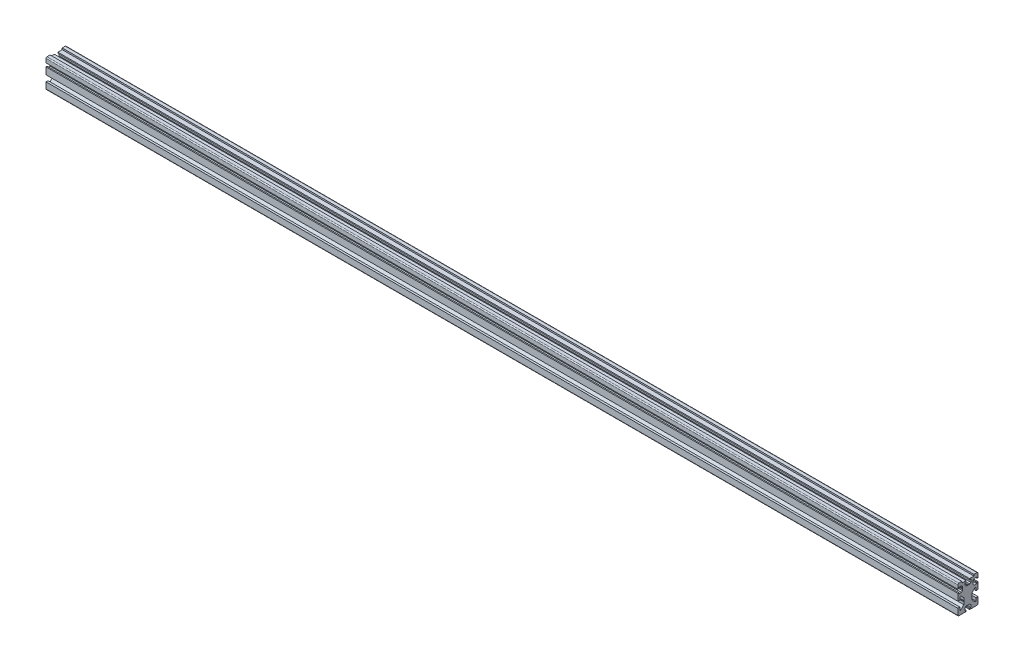
SolidWorks part; units mm, degrees
ref_plane "Front Plane" through (0, 0, 0) normal (0, 0, 1) x (1, 0, 0)
ref_plane "Top Plane" through (0, 0, 0) normal (0, 1, 0) x (1, 0, 0)
ref_plane "Right Plane" through (0, 0, 0) normal (1, 0, 0) x (0, 0, -1)
ref_plane "Plane1" through (24, 0, 0) normal (1, 0, 0) x (0, 0, -1)
ref_plane "Plane2" through (1000, 0, 0) normal (1, 0, 0) x (0, 0, -1)
ref_plane "Plane3" through (925, 0, 0) normal (1, 0, 0) x (0, 0, -1)
ref_plane "Plane4" through (474.5, 0, 0) normal (1, 0, 0) x (0, 0, -1)
sketch "Sketch1" plane through (24, 0, 0) normal (1, 0, 0) x (0, 0, -1)
  line L0 (-5.3, 9.35) -> (-5.3, 8.0196)
  line L1 (-5.3, 8.0196) -> (-5, 7.5)
  line L2 (-5, 7.5) -> (-5.3, 6.9804)
  line L3 (-5.3, 6.9804) -> (-5.3, 5.65)
  line L4 (-5.3, 5.65) -> (-6.3, 4.65)
  line L5 (-6.3, 4.65) -> (-8.9, 4.65)
  line L6 (-8.9, 4.65) -> (-8.9, 5.8)
  line L7 (-8.9, 5.8) -> (-10, 5.8)
  line L8 (-10, 5.8) -> (-10, -1)
  line L9 (-10, -1) -> (-8, -1)
  line L10 (-8, -1) -> (-8, 2)
  line L11 (-8, 2) -> (-7, 2)
  line L12 (-7, 2) -> (-4, -1)
  line L13 (-4, -1) -> (-4, -3.4804)
  line L14 (-4, -3.4804) -> (-3.7, -4)
  line L15 (-3.7, -4) -> (-4, -4.5196)
  line L16 (-4, -4.5196) -> (-4, -7)
  line L17 (-4, -7) -> (-7, -10)
  line L18 (-7, -10) -> (-8, -10)
  line L19 (-8, -10) -> (-8, -7)
  line L20 (-8, -7) -> (-10, -7)
  line L21 (-10, -7) -> (-10, -13)
  line L22 (-9, -14) -> (-1.7, -14)
  line L23 (-1.7, -14) -> (-1.7, -12.9)
  line L24 (-1.7, -12.9) -> (-2.85, -12.9)
  line L25 (-2.85, -12.9) -> (-2.85, -10.3)
  line L26 (-2.85, -10.3) -> (-1.85, -9.3)
  line L27 (-1.85, -9.3) -> (-0.5196, -9.3)
  line L28 (-0.5196, -9.3) -> (0, -9)
  line L29 (0, -9) -> (0.5196, -9.3)
  line L30 (0.5196, -9.3) -> (1.85, -9.3)
  line L31 (1.85, -9.3) -> (2.85, -10.3)
  line L32 (2.85, -10.3) -> (2.85, -12.9)
  line L33 (2.85, -12.9) -> (1.7, -12.9)
  line L34 (1.7, -12.9) -> (1.7, -14)
  line L35 (1.7, -14) -> (9, -14)
  line L36 (10, -13) -> (10, -7)
  line L37 (-5, 7.5) -> (-10, 7.5) construction
  line L38 (-3.7, -4) -> (-10, -4) construction
  line L39 (5, 7.5) -> (10, 7.5) construction
  line L40 (6.3, 10.35) -> (5.3, 9.35)
  line L41 (8.9, 10.35) -> (6.3, 10.35)
  line L42 (8.9, 9.2) -> (8.9, 10.35)
  line L43 (10, 9.2) -> (8.9, 9.2)
  line L44 (8.9, 5.8) -> (10, 5.8)
  line L45 (8.9, 4.65) -> (8.9, 5.8)
  line L46 (6.3, 4.65) -> (8.9, 4.65)
  line L47 (5.3, 5.65) -> (6.3, 4.65)
  line L48 (5.3, 6.9804) -> (5.3, 5.65)
  line L49 (10, -1) -> (10, 5.8)
  line L50 (5, 7.5) -> (5.3, 6.9804)
  line L51 (5.3, 8.0196) -> (5, 7.5)
  line L52 (5.3, 9.35) -> (5.3, 8.0196)
  line L53 (3.7, -4) -> (10, -4) construction
  line L54 (8, -7) -> (10, -7)
  line L55 (8, -10) -> (8, -7)
  line L56 (7, -10) -> (8, -10)
  line L57 (4, -7) -> (7, -10)
  line L58 (4, -4.5196) -> (4, -7)
  line L59 (3.7, -4) -> (4, -4.5196)
  line L60 (4, -3.4804) -> (3.7, -4)
  line L61 (4, -1) -> (4, -3.4804)
  line L62 (7, 2) -> (4, -1)
  line L63 (8, 2) -> (7, 2)
  line L64 (10, 9.2) -> (10, 13)
  line L65 (6, 14) -> (9, 14)
  line L66 (-10, 13) -> (-10, 9.2)
  line L67 (-10, 9.2) -> (-8.9, 9.2)
  line L68 (-8.9, 9.2) -> (-8.9, 10.35)
  line L69 (-8.9, 10.35) -> (-6.3, 10.35)
  line L70 (-6.3, 10.35) -> (-5.3, 9.35)
  line L71 (-1.7, 12.5) -> (-6, 12.5)
  line L72 (-6, 12.5) -> (-6, 14)
  line L73 (-9, 14) -> (-6, 14)
  line L74 (6, 14) -> (6, 12.5)
  line L75 (6, 12.5) -> (1.7, 12.5)
  line L76 (1.7, 12.5) -> (1.7, 11.4)
  line L77 (1.7, 11.4) -> (2.85, 11.4)
  line L78 (2.85, 11.4) -> (2.85, 8.8)
  line L79 (2.85, 8.8) -> (1.85, 7.8)
  line L80 (1.85, 7.8) -> (0.5196, 7.8)
  line L81 (0.5196, 7.8) -> (0, 7.5)
  line L82 (0, 7.5) -> (-0.5196, 7.8)
  line L83 (-0.5196, 7.8) -> (-1.85, 7.8)
  line L84 (-1.85, 7.8) -> (-2.85, 8.8)
  line L85 (-2.85, 8.8) -> (-2.85, 11.4)
  line L86 (-2.85, 11.4) -> (-1.7, 11.4)
  line L87 (-1.7, 11.4) -> (-1.7, 12.5)
  line L88 (10, 0) -> (-10, 0) construction
  line L89 (0, 14) -> (0, -14) construction
  line L90 (11, 0) -> (-11, 0) construction
  line L91 (0, 15.4) -> (0, -15.4) construction
  line L92 (-6, 14) -> (6, 14) construction
  line L93 (-1.7, -14) -> (1.7, -14) construction
  line L94 (8, -1) -> (8, 2)
  line L95 (10, -1) -> (8, -1)
  arc A0 (-10, -13) -> (-9, -14) centre (-9, -13) ccw
  arc A1 (9, -14) -> (10, -13) centre (9, -13) ccw
  arc A2 (10, 13) -> (9, 14) centre (9, 13) ccw
  arc A3 (-9, 14) -> (-10, 13) centre (-9, 13) ccw
  point P46 (0, 12.5)
  dimension "FIX_21" = 2
  dimension "FIX_6" = 1
  dimension "FIX_3" = 14
  dimension "FIX_4" = 28
  dimension "FIX_5" = 20
  dimension "FIX_7" = 12
  dimension "FIX_8" = 1.5
  dimension "FIX_17" = 10
  dimension "FIX_18" = 11.5
  dimension "FIX_19" = 6
  dimension "FIX_20" = 12
  dimension "FIX_22" = 4
extrude "Boss-Extrude1" add sketch "Sketch1" along normal up to surface (901 mm away) up to plane "Plane3"
ref_plane "Plane5" through (0, 0, 10) normal (0, 0, 1) x (1, 0, 0)
sketch "Sketch2" [suppressed] plane through (0, 0, 10) normal (0, 0, 1) x (1, 0, 0)
  line L0 (0, -11) -> (0, 11) construction
  circle A0 centre (85, 7.5) radius 3.55
  dimension "FIX_25" = 7.1
  dimension "FYA" = 85
extrude "Cut-Extrude1" [suppressed] cut sketch "Sketch2" against normal up to surface (1.1 mm away)
sketch "Sketch3" [suppressed] plane through (0, 0, 10) normal (0, 0, 1) x (1, 0, 0)
  circle A0 centre (85, -4) radius 6.05
  dimension "FIX_26" = 12.1
extrude "Cut-Extrude2" [suppressed] cut sketch "Sketch3" against normal up to surface (2 mm away)
sketch "Sketch4" [suppressed] plane through (0, 0, 10) normal (0, 0, 1) x (1, 0, 0)
  line L0 (0, -11) -> (0, 11) construction
  circle A0 centre (820, 7.5) radius 3.55
  dimension "FIX_27" = 7.1
  dimension "FYB" = 820
extrude "Cut-Extrude3" [suppressed] cut sketch "Sketch4" against normal up to surface (1.1 mm away)
sketch "Sketch5" [suppressed] plane through (0, 0, 10) normal (0, 0, 1) x (1, 0, 0)
  circle A0 centre (820, -4) radius 6.05
  dimension "FIX_28" = 12.1
extrude "Cut-Extrude4" [suppressed] cut sketch "Sketch5" against normal up to surface (2 mm away)
